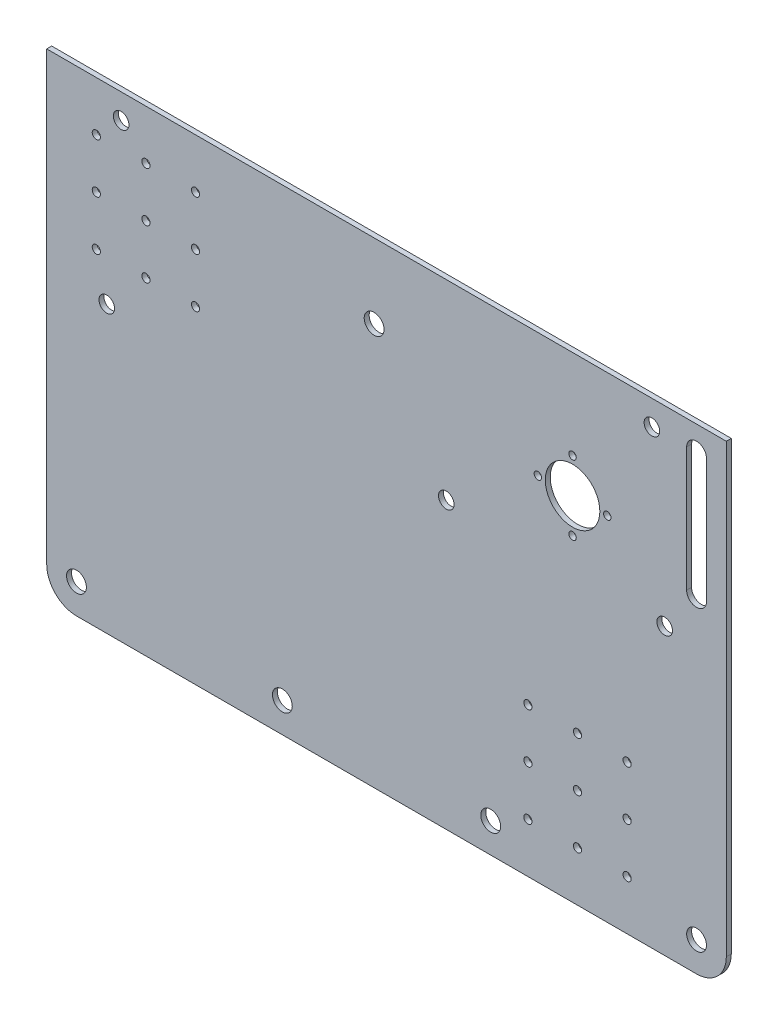
SolidWorks part; units mm, degrees
ref_plane "Front Plane" through (0, 0, 0) normal (0, 0, 1) x (1, 0, 0)
ref_plane "Top Plane" through (0, 0, 0) normal (0, 1, 0) x (1, 0, 0)
ref_plane "Right Plane" through (0, 0, 0) normal (1, 0, 0) x (0, 0, -1)
sketch "Sketch1" plane through (0, 0, 0) normal (0, 0, 1) x (1, 0, 0)
  line L0 (55, 0) -> (-55, 0) construction
  line L1 (0, 53.2731) -> (0, -38.9774) construction
  line L2 (0, -55) -> (0, 55) construction
  line L3 (-125, -12) -> (125, -12)
  line L4 (121, 120) -> (129, 120)
  line L5 (121, 120) -> (121, 170)
  line L6 (121, 170) -> (129, 170)
  line L7 (129, 120) -> (129, 170)
  line L8 (121, 120) -> (129, 170) construction
  line L9 (121, 170) -> (129, 120) construction
  line L10 (158.4448, 180) -> (-53.9982, 180)
  line L11 (137, 0) -> (137, 180)
  line L12 (137, 180) -> (158.4448, 180)
  line L13 (-53.9982, 180) -> (-137, 180)
  line L14 (-137, 180) -> (-137, 0)
  circle A0 centre (-125, 0) radius 4
  circle A1 centre (125, 0) radius 4
  circle A2 centre (125, 170) radius 4
  circle A3 centre (75, 130) radius 11
  circle A4 centre (-5, 150) radius 4
  circle A5 centre (125, 120) radius 4
  arc A6 (-125, -12) -> (-137, 0) centre (-125, 0) cw
  arc A7 (125, -12) -> (137, 0) centre (125, 0) ccw
  circle A8 centre (75, 130) radius 14 construction
  circle A9 centre (75, 144) radius 1.5
  circle A10 centre (89, 130) radius 1.5
  circle A11 centre (75, 116) radius 1.5
  circle A12 centre (61, 130) radius 1.5
  circle A13 centre (24.0972, 103) radius 3.15
  circle A15 centre (-112.7883, 103) radius 3.15
  circle A16 centre (112.1538, 103) radius 3.15
  circle A17 centre (-107, 170) radius 3.15
  circle A18 centre (107, 170) radius 3.15
  circle A19 centre (-117, 160) radius 1.65
  circle A20 centre (-117, 140) radius 1.65
  circle A21 centre (-117, 120) radius 1.65
  circle A22 centre (-97, 160) radius 1.65
  circle A23 centre (-97, 140) radius 1.65
  circle A24 centre (-97, 120) radius 1.65
  circle A25 centre (-77, 160) radius 1.65
  circle A26 centre (-77, 140) radius 1.65
  circle A27 centre (-77, 120) radius 1.65
  circle A28 centre (97, 8) radius 1.65
  circle A29 centre (77, 8) radius 1.65
  circle A30 centre (57, 8) radius 1.65
  circle A31 centre (97, 28) radius 1.65
  circle A32 centre (77, 28) radius 1.65
  circle A33 centre (57, 28) radius 1.65
  circle A34 centre (97, 48) radius 1.65
  circle A35 centre (77, 48) radius 1.65
  circle A36 centre (57, 48) radius 1.65
  circle A37 centre (-42, 0) radius 4
  circle A38 centre (42, 0) radius 4
  point P17 (125, 145)
  point P44 (75, 130)
  point P95 (0, 0)
  dimension "D2" = 8
  dimension "D4" = 22
  dimension "D11" = 12
  dimension "D13" = 12
  dimension "D14" = 28
  dimension "D15" = 3
  dimension "D18" = 6.3
  dimension "D24" = 3.3
  dimension "D25" = 3
  dimension "D26" = 3.3
  dimension "D30" = 8
  dimension "D31" = 8
  dimension "D1" = 250
  dimension "D3" = 250
  dimension "D5" = 120
  dimension "D6" = 150
  dimension "D7" = 130
  dimension "D8" = 200
  dimension "D9" = 145
  dimension "D10" = 50
  dimension "D12" = 10
  dimension "D17" = 10
  dimension "D19" = 30
  dimension "D20" = 30
  dimension "D21" = 20
  dimension "D22" = 20
  dimension "D27" = 40
  dimension "D28" = 20
  dimension "D32" = 83
  dimension "D33" = 83
  dimension "D23" = 3
  dimension "D29" = 3
  dimension "D16" = 4
extrude "Boss-Extrude1" add sketch "Sketch1" along normal blind 2 contours L3 A7 L11 L10 L13 L14 A6 A38 A37 A36 A35 A34 A33 A32 A31 A30 A29 A28 A27 A26 A25 A24 A23 A22 A21 A20 A19 A18 A17
